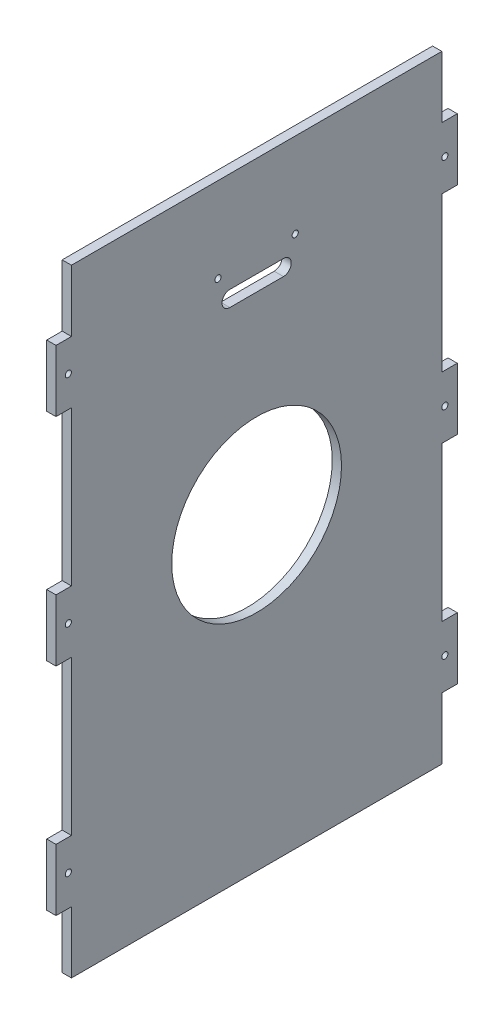
SolidWorks part; units mm, degrees
ref_plane "Front Plane" through (0, 0, 0) normal (1, 0, 0) x (0, 1, 0)
ref_plane "Top Plane" through (0, 0, 0) normal (0, 0, 1) x (0, 1, 0)
ref_plane "Right Plane" through (0, 0, 0) normal (0, 1, 0) x (-1, 0, 0)
sketch "Sketch1" plane through (0, 0, 0) normal (1, 0, 0) x (0, 1, 0)
  line L0 (-80, 60) -> (-80, 65)
  line L1 (-100, 60) -> (-80, 60)
  line L2 (-100, 60) -> (-100, -60)
  line L3 (-100, -60) -> (-80, -60)
  line L4 (100, 60) -> (100, -60)
  line L5 (-80, 65) -> (-60, 65)
  line L6 (-60, 65) -> (-60, 60)
  line L7 (0, 99.2979) -> (0, 56.4065) construction
  line L8 (232.3568, 0) -> (100, 0) construction
  line L9 (-10, 60) -> (-10, 65)
  line L10 (-10, 65) -> (10, 65)
  line L11 (10, 65) -> (10, 60)
  line L12 (80, 60) -> (80, 65)
  line L13 (80, 65) -> (60, 65)
  line L14 (60, 65) -> (60, 60)
  line L15 (80, -60) -> (80, -65)
  line L16 (80, -65) -> (60, -65)
  line L17 (60, -65) -> (60, -60)
  line L18 (10, -65) -> (10, -60)
  line L19 (-10, -65) -> (10, -65)
  line L20 (-10, -60) -> (-10, -65)
  line L21 (-80, -60) -> (-80, -65)
  line L22 (-80, -65) -> (-60, -65)
  line L23 (-60, -65) -> (-60, -60)
  line L24 (80, 60) -> (100, 60)
  line L25 (10, 60) -> (60, 60)
  line L26 (-60, 60) -> (-10, 60)
  line L27 (-60, -60) -> (-10, -60)
  line L28 (10, -60) -> (60, -60)
  line L29 (80, -60) -> (100, -60)
  line L35 (0, -54.4487) -> (0, -106.0143) construction
  line L41 (-100, 0) -> (-207.1848, 0) construction
  circle A48 centre (-70, 61) radius 1
  circle A49 centre (70, 61) radius 1
  circle A50 centre (0, 61) radius 1
  circle A51 centre (70, -61) radius 1
  circle A52 centre (0, -61) radius 1
  circle A53 centre (-70, -61) radius 1
  point P6 (-100, 0)
  point P17 (0, 65)
  dimension "D11" = 2
  dimension "D13" = 2
  dimension "D1" = 200
  dimension "D2" = 120
  dimension "D3" = 20
  dimension "D4" = 5
  dimension "D5" = 20
  dimension "D6" = 20
  dimension "D7" = 5
  dimension "D12" = 4
extrude "Boss-Extrude1" add sketch "Sketch1" along normal blind 3
sketch "Sketch2" plane through (3, 0, 0) normal (1, 0, 0) x (0, 1, 0)
  line L0 (100, 60) -> (100, -60) construction
  line L1 (70, 15) -> (100, 15) construction
  line L2 (70, 15) -> (70, -15) construction
  line L3 (70, -15) -> (100, -15) construction
  line L4 (100, 15) -> (100, -15) construction
  line L5 (64.9963, 8.6868) -> (64.9963, -8.6868) construction
  line L6 (67.5275, 8.6868) -> (67.5275, -8.6868)
  line L7 (62.4651, 8.6868) -> (62.4651, -8.6868)
  line L8 (127.2442, 0) -> (-5.368, 0) construction
  circle A0 centre (0, 0) radius 27.5
  arc A1 (67.5275, 8.6868) -> (62.4651, 8.6868) centre (64.9963, 8.6868) ccw
  arc A2 (62.4651, -8.6868) -> (67.5275, -8.6868) centre (64.9963, -8.6868) ccw
  circle A3 centre (72.5, -12.5) radius 1
  circle A4 centre (72.5, 12.5) radius 1
  point P9 (100, 0)
  point P10 (100, 0)
  point P13 (64.9963, 0)
  dimension "D1" = 55
  dimension "D4" = 2
  dimension "D2" = 30
  dimension "D3" = 30
  dimension "D5" = 2.5
  dimension "D6" = 2.5
extrude "Cut-Extrude1" cut sketch "Sketch2" against normal blind 3
